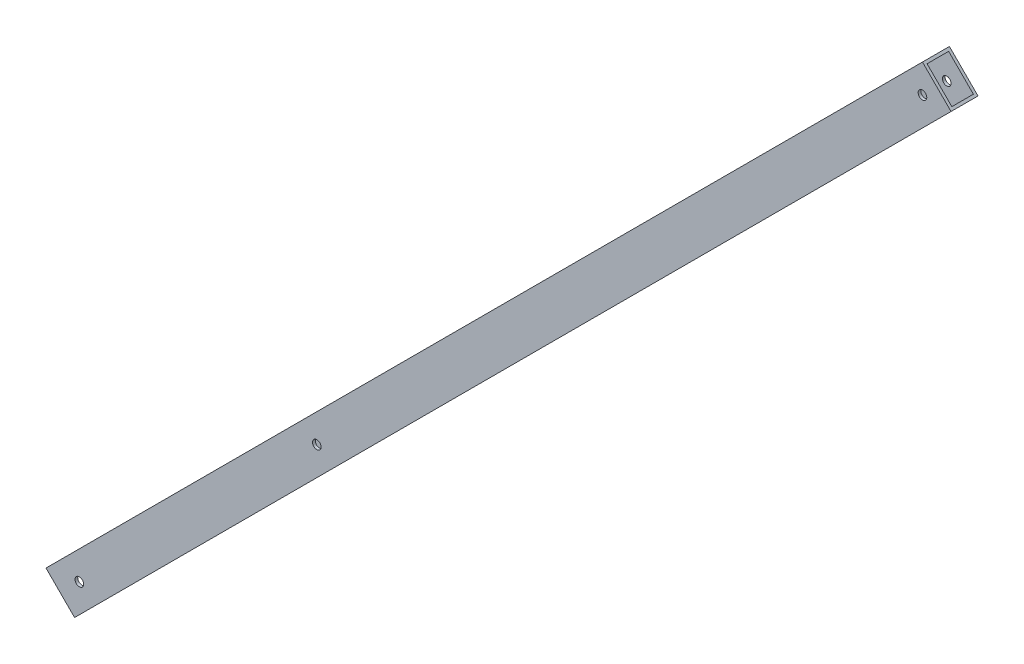
SolidWorks part; units mm, degrees
ref_plane "正面" through (0, 0, 0) normal (0, 0, 1) x (1, 0, 0)
ref_plane "平面" through (0, 0, 0) normal (0, 1, 0) x (1, 0, 0)
ref_plane "右側面" through (0, 0, 0) normal (1, 0, 0) x (0, 0, -1)
sketch "ｽｹｯﾁ1" plane through (0, 0, 0) normal (0, 0, 1) x (1, 0, 0)
  line L0 (325.2691, 325.2691) -> (335.8757, 314.6625)
  line L2 (335.8757, 314.6625) -> (10.6066, -10.6066)
  line L3 (10.6066, -10.6066) -> (0, 0)
  line L4 (0, 0) -> (325.2691, 325.2691)
  circle A0 centre (100.5191, 89.9125) radius 1.6
  circle A2 centre (12.3744, 1.7678) radius 1.6
  circle A4 centre (325.2691, 314.6625) radius 1.6
  dimension "D3" = 7.5
  dimension "D6" = 7.5
  dimension "D7" = 3.2
  dimension "D5" = 450
  dimension "D2" = 7.5
  dimension "D4" = 134.6555
  dimension "D9" = 3.2
  dimension "D11" = 7.5
  dimension "D12" = 3.2
  dimension "D1" = 15
  dimension "D8" = 460
  dimension "D10" = 0
  dimension "D13" = 325.2691
extrude "ﾎﾞｽ - 押し出し1" add sketch "ｽｹｯﾁ1" along normal blind 10
sketch "ｽｹｯﾁ2" plane through (0, 0, 0) normal (-0.7071, -0.7071, 0) x (0, 0, 1)
  line L8 (1, -1) -> (1, -14)
  line L9 (1, -14) -> (9, -14)
  line L10 (9, -14) -> (9, -1)
  line L11 (9, -1) -> (1, -1)
  line L12 (1, -1) -> (1, -14)
  line L13 (1, -14) -> (9, -14)
  line L14 (9, -14) -> (9, -1)
  line L15 (9, -1) -> (1, -1)
  dimension "D1" = 1
extrude "ｶｯﾄ - 押し出し1" cut sketch "ｽｹｯﾁ2" against normal blind 1000
